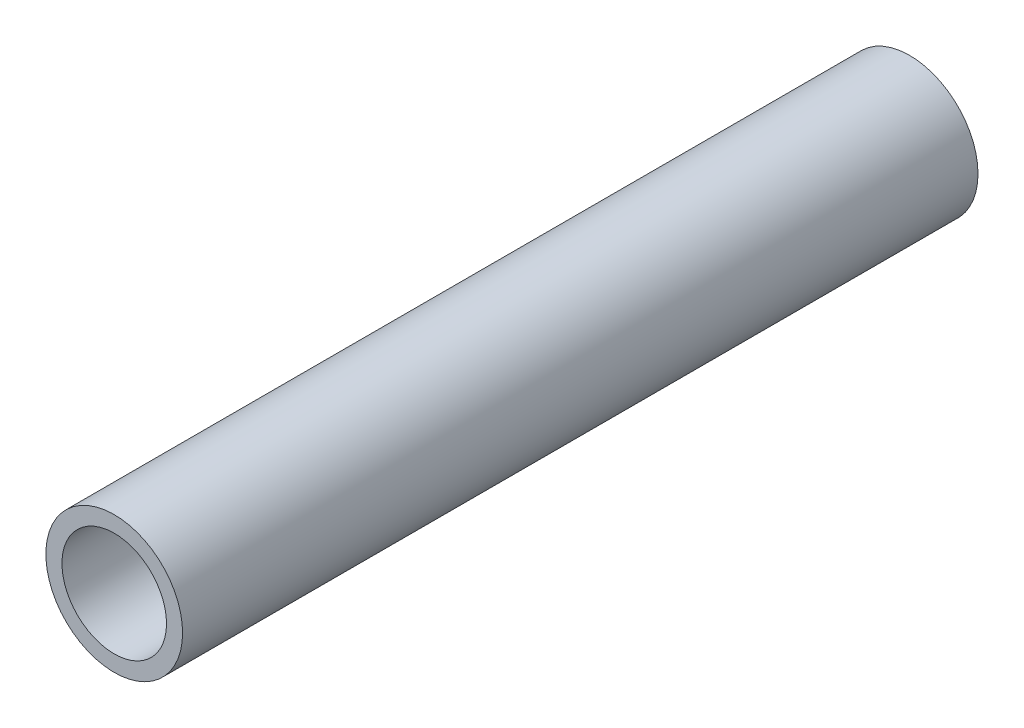
SolidWorks part; units mm, degrees
ref_plane "Piano frontale" through (0, 0, 0) normal (0, 0, 1) x (1, 0, 0)
ref_plane "Piano superiore" through (0, 0, 0) normal (0, 1, 0) x (1, 0, 0)
ref_plane "Piano destro" through (0, 0, 0) normal (1, 0, 0) x (0, 0, -1)
sketch "Schizzo1" plane through (0, 0, 0) normal (0, 0, 1) x (1, 0, 0)
  circle A0 centre (0, 0) radius 3.25
  circle A1 centre (0, 0) radius 4.25
  dimension "D1" = 6.5
  dimension "D2" = 1
extrude "Estrusione-Estrusione1" add sketch "Schizzo1" along normal blind 49.45
